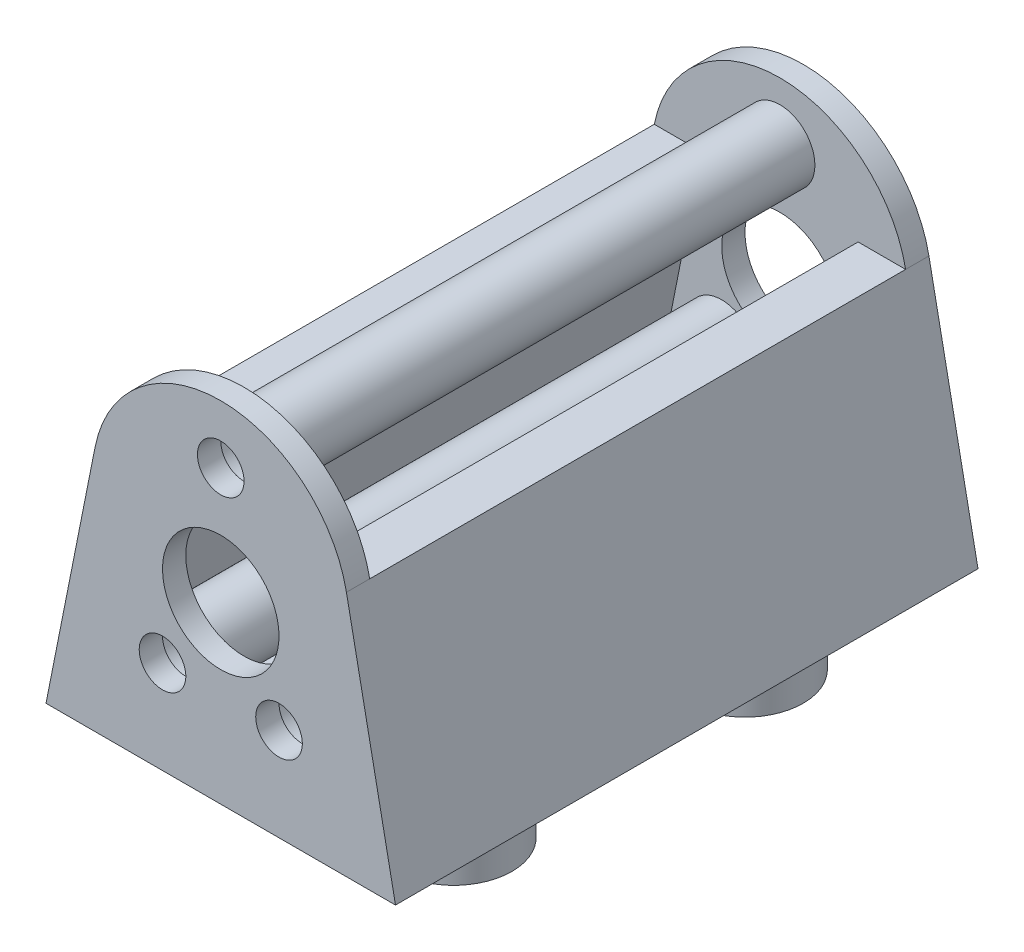
SolidWorks part; units mm, degrees
ref_plane "Front Plane" through (0, 0, 0) normal (0, 0, 1) x (1, 0, 0)
ref_plane "Top Plane" through (0, 0, 0) normal (0, 1, 0) x (1, 0, 0)
ref_plane "Right Plane" through (0, 0, 0) normal (1, 0, 0) x (0, 0, -1)
sketch "Sketch1" plane through (0, 0, 0) normal (0, 0, 1) x (1, 0, 0)
  line L0 (-15, 0) -> (15, 0)
  line L1 (0, 0) -> (0, 30) construction
  line L2 (15, 0) -> (10.7881, 21.1485)
  line L3 (-15, 0) -> (-10.7881, 21.1485)
  line L4 (-5, 8) -> (5, 8) construction
  arc A0 (10.7881, 21.1485) -> (-10.7881, 21.1485) centre (0, 19) ccw
  circle A1 centre (0, 15) radius 5
  circle A2 centre (5, 8) radius 2
  circle A3 centre (-5, 8) radius 2
  circle A4 centre (0, 25) radius 2
  point P4 (0, 0)
  point P15 (0, 8)
  dimension "D3" = 22
  dimension "D4" = 10
  dimension "D5" = 4
  dimension "D8" = 4
  dimension "D1" = 30
  dimension "D2" = 30
  dimension "D6" = 10
  dimension "D7" = 8
  dimension "D9" = 5
extrude "Boss-Extrude1" add sketch "Sketch1" along normal blind 2
ref_plane "Plane1" through (0, 0, 50) normal (0, 0, -1) x (-1, 0, 0)
sketch "Sketch2" plane through (0, 0, 50) normal (0, 0, -1) x (-1, 0, 0)
  line L3 (-10.7881, 21.1485) -> (-15, 0)
  line L4 (15, 0) -> (10.7881, 21.1485)
  line L5 (-15, 0) -> (15, 0)
  line L6 (-10.7881, 21.1485) -> (-15, 0)
  line L7 (15, 0) -> (10.7881, 21.1485)
  line L8 (-15, 0) -> (15, 0)
  circle A0 centre (-5, 8) radius 2 construction
  arc A1 (10.7881, 21.1485) -> (-10.7881, 21.1485) centre (0, 19) ccw
  arc A2 (10.7881, 21.1485) -> (-10.7881, 21.1485) centre (0, 19) ccw
  circle A3 centre (5, 8) radius 2 construction
  circle A4 centre (0, 25) radius 2 construction
  circle A5 centre (0, 15) radius 5 construction
  circle A6 centre (-5, 8) radius 2
  circle A7 centre (5, 8) radius 2
  circle A8 centre (0, 25) radius 2
  circle A9 centre (0, 15) radius 5
  dimension "D1" = 0
extrude "Boss-Extrude2" add sketch "Sketch2" along normal blind 2 separate body
sketch "Sketch3" plane through (0, 0, 2) normal (0, 0, 1) x (1, 0, 0)
  line L0 (0, 0) -> (0, 20.5252) construction
  line L1 (-15, 0) -> (15, 0) construction
  circle A0 centre (5, 8) radius 3
  circle A1 centre (5, 8) radius 2.5
  circle A2 centre (0, 25) radius 3
  circle A3 centre (0, 25) radius 2.5
  circle A4 centre (-5, 8) radius 3
  circle A5 centre (-5, 8) radius 2.5
  dimension "D1" = 6
  dimension "D3" = 6
  dimension "D2" = 0.5
  dimension "D4" = 0.5
extrude "Boss-Extrude3" add sketch "Sketch3" along normal up to surface (46 mm away) up to face at (-2, 25, 48)
sketch "Sketch4" plane through (0, 0, 2) normal (0, 0, 1) x (1, 0, 0)
  line L0 (-15, 0) -> (15, 0) construction
  line L1 (-15, 0) -> (15, 0)
  line L2 (14.2034, 4) -> (-14.2034, 4)
  line L3 (15, 0) -> (10.7881, 21.1485) construction
  line L4 (-10.7881, 21.1485) -> (-15, 0) construction
  line L5 (14.2034, 4) -> (15, 0)
  line L6 (-14.2034, 4) -> (-15, 0)
  line L7 (15, 0) -> (10.7881, 21.1485)
  line L8 (10.1248, 4) -> (6.7096, 21.1485)
  line L9 (11.077, -0.7813) -> (6.8652, 20.3672) construction
  line L10 (10.7881, 21.1485) -> (6.7096, 21.1485)
  line L11 (0, 0) -> (0, 17.8186) construction
  line L12 (-15, 0) -> (-10.7881, 21.1485)
  line L13 (-10.7881, 21.1485) -> (-6.7096, 21.1485)
  line L14 (-10.1248, 4) -> (-6.7096, 21.1485)
  line L15 (10.7881, 21.1485) -> (14.2034, 4)
  line M10 (15, 0) -> (10.7881, 21.1485)
  line M12 (-10.7881, 21.1485) -> (-15, 0)
  line M13 (-15, 0) -> (15, 0)
  dimension "D1" = 4
  dimension "D2" = 4
extrude "Boss-Extrude5" add sketch "Sketch4" along normal up to surface (46 mm away) contours L2 L14 L13 M12 | L10 L8 L2 M10 | L2 M10 M12 M13 up to face at (-8, 8, 48)
sketch "Sketch5" plane through (0, 0, 0) normal (0, 0, -1) x (-1, 0, 0)
  circle A0 centre (0, 15) radius 3.0123
ref_plane "Plane2" through (0, 15, 0) normal (0, 1, 0) x (1, 0, 0)
sketch "Sketch6" plane through (0, 15, 0) normal (0, 1, 0) x (1, 0, 0)
  line L0 (0, 0) -> (0, -25) construction
sketch "Sketch7" plane through (0, 0, 0) normal (0, -1, 0) x (1, 0, 0)
  line L0 (0, 50) -> (0, 0) construction
  line L1 (15, 50) -> (-15, 50) construction
  line L2 (0, 25) -> (15, 25) construction
  line L3 (15, 50) -> (15, 0) construction
  line L4 (7.5, 25) -> (7.5, 50) construction
  circle A0 centre (7.5, 37.5) radius 5
  circle A1 centre (7.5, 37.5) radius 2.5
  circle A2 centre (7.5, 12.5) radius 2.5
  circle A3 centre (7.5, 12.5) radius 5
  circle A4 centre (-7.5, 12.5) radius 2.5
  circle A5 centre (-7.5, 12.5) radius 5
  circle A6 centre (-7.5, 37.5) radius 2.5
  circle A7 centre (-7.5, 37.5) radius 5
  dimension "D1" = 10
  dimension "D2" = 5
extrude "Boss-Extrude6" add sketch "Sketch7" along normal blind 5
